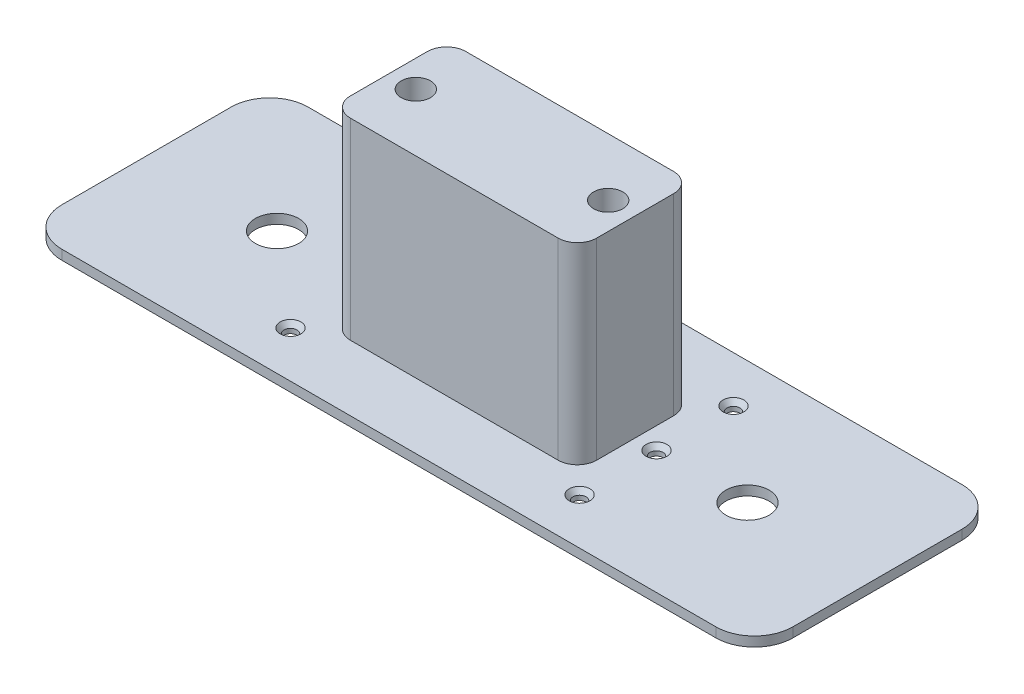
SolidWorks part; units mm, degrees
material "ABS"
ref_plane "Front" through (0, 0, 0) normal (0, 0, 1) x (1, 0, 0)
ref_plane "Top" through (0, 0, 0) normal (0, 1, 0) x (1, 0, 0)
ref_plane "Right" through (0, 0, 0) normal (1, 0, 0) x (0, 0, -1)
sketch "Sketch1" plane through (0, 0, 0) normal (0, 1, 0) x (1, 0, 0)
  line L1 (-60.325, 20.32) -> (60.325, 20.32)
  line L2 (-60.325, 20.32) -> (-60.325, -20.32)
  line L3 (-60.325, -20.32) -> (60.325, -20.32)
  line L4 (60.325, 20.32) -> (60.325, -20.32)
  line L5 (-60.325, 20.32) -> (60.325, -20.32) construction
  line L6 (-60.325, -20.32) -> (60.325, 20.32) construction
  point P0 (0, 0)
  dimension "D1" = 120.65
  dimension "D2" = 40.64
extrude "Boss-Extrude1" add sketch "Sketch1" along normal blind 1.5875
fillet "Fillet1" radius 6.35 4 edges at (-60.325, 0.7937, 20.32) (-60.325, 0.7937, -20.32) (60.325, 0.7937, -20.32) (60.325, 0.7937, 20.32)
sketch "Sketch2" plane through (0, 1.5875, 0) normal (0, 1, 0) x (1, 0, 0)
  line L1 (-20.32, 9.525) -> (20.32, 9.525)
  line L2 (-20.32, 9.525) -> (-20.32, -9.525)
  line L3 (-20.32, -9.525) -> (20.32, -9.525)
  line L4 (20.32, 9.525) -> (20.32, -9.525)
  line L5 (-20.32, 9.525) -> (20.32, -9.525) construction
  line L6 (-20.32, -9.525) -> (20.32, 9.525) construction
  point P0 (0, 0)
  point P6 (0, 0)
  dimension "D1" = 40.64
  dimension "D2" = 19.05
extrude "Boss-Extrude2" add sketch "Sketch2" along normal blind 31.75
fillet "Fillet2" radius 3.175 4 edges at (-20.32, 17.4625, -9.525) (-20.32, 17.4625, 9.525) (20.32, 17.4625, 9.525) (20.32, 17.4625, -9.525)
sketch "Sketch3" plane through (0, 33.3375, 0) normal (0, 1, 0) x (1, 0, 0)
  line L0 (-15.875, 0) -> (15.875, 0) construction
  point P4 (0, 0)
  point P6 (-15.875, 0)
  point P7 (15.875, 0)
  dimension "D1" = 31.75
hole_wizard "#10 Clearance Hole1" positions "Sketch4" profile "Sketch5" hole size "#10" standard "ANSI Inch"
sketch "Sketch4" plane through (0, 33.3375, 0) normal (0, 1, 0) x (1, 0, 0)
  point P0 (-15.875, 0)
  point P3 (15.875, 0)
sketch "Sketch5" plane through (-15.875, 33.3375, 0) normal (1, 0, 0) x (0, 0, 1)
  line L0 (0, 0) -> (0, 26.8499)
  line L1 (0, 26.8499) -> (2.413, 25.4)
  line L2 (2.413, 25.4) -> (2.413, 0)
  line L5 (2.413, 0) -> (0, 0)
  line L10 (0, 26.8499) -> (-2.413, 25.4) construction
  line L11 (0, -6.35) -> (0, 107.95) construction
  dimension "Hole Dia." = 4.826
  dimension "Hole Depth" = 25.4
  dimension "Drill Angle" = 118
sketch "Sketch10" plane through (0, 0, 0) normal (0, -1, 0) x (1, 0, 0)
  line L1 (0, -50) -> (0, 50) construction
  circle A0 centre (23.85, -12.7) radius 1.0795 construction
  circle A1 centre (23.85, 12.7) radius 1.0795 construction
  circle A2 centre (23.85, 0) radius 1.0795 construction
  point P0 (23.85, 12.7)
  point P1 (23.85, 0)
  point P2 (23.85, -12.7)
  point P18 (-23.85, -12.7)
  point P19 (-23.85, 0)
  point P20 (-23.85, 12.7)
hole_wizard "#2 Clearance Hole1" positions "Sketch11" profile "Sketch12" hole size "#2" standard "ANSI Inch" end condition through all
sketch "Sketch11" plane through (0, 1.5875, 0) normal (0, 1, 0) x (1, 0, 0)
  point P0 (-23.85, 12.7)
  point P3 (-23.85, 0)
  point P6 (-23.85, -12.7)
  point P9 (23.85, -12.7)
  point P12 (23.85, 0)
  point P15 (23.85, 12.7)
sketch "Sketch12" plane through (-23.85, 1.5875, -12.7) normal (1, 0, 0) x (0, 0, 1)
  line L0 (0, 0) -> (0, 1.5875)
  line L1 (0, 1.5875) -> (1.0795, 1.5875)
  line L2 (1.0795, 1.5875) -> (1.0795, 0.8275)
  line L3 (1.0795, 0.8275) -> (1.7145, 0)
  line L5 (1.7145, 0) -> (0, 0)
  line L6 (-1.0795, 0.8275) -> (-1.7145, 0) construction
  line L11 (0, -6.35) -> (0, 107.95) construction
  dimension "Thru Hole Dia." = 2.159
  dimension "Thru Hole Depth" = 1.5875
  dimension "Near C'Sink Dia." = 3.429
  dimension "Near C'Sink Angle" = 75
sketch "Sketch13" plane through (0, 0, 0) normal (0, -1, 0) x (-1, 0, 0)
  line L0 (0, 50) -> (0, -50) construction
  circle A0 centre (38.825, 0.0428) radius 3.843 construction
  circle A1 centre (38.825, 0.0428) radius 3.575
  circle A2 centre (-38.825, 0.0428) radius 3.843 construction
  circle A3 centre (-38.825, 0.0428) radius 3.575
  dimension "D1" = 7.15
extrude "Cut-Extrude1" cut sketch "Sketch13" against normal through all
